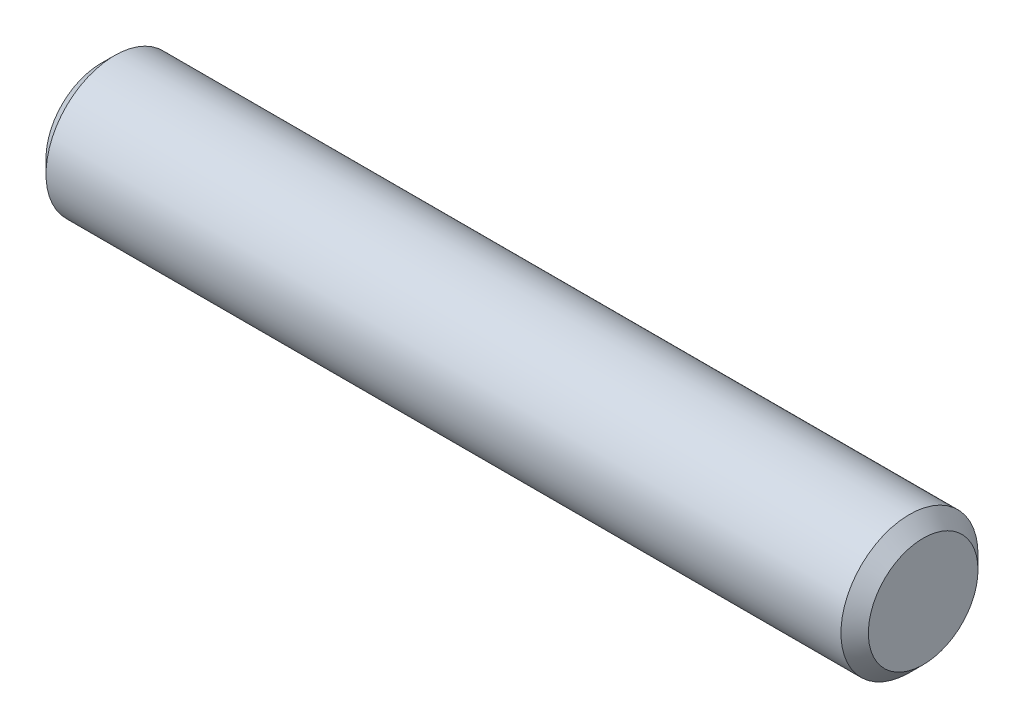
SolidWorks part; units mm, degrees
ref_plane "Front" through (0, 0, 0) normal (0, 0, 1) x (1, 0, 0)
ref_plane "Top" through (0, 0, 0) normal (0, 1, 0) x (1, 0, 0)
ref_plane "Right" through (0, 0, 0) normal (1, 0, 0) x (0, 0, -1)
sketch "Sketch1" plane through (0, 0, 0) normal (0, 0, 1) x (1, 0, 0)
  line L0 (-19.05, 0) -> (19.05, 0) construction
  line L1 (19.05, 3.175) -> (19.05, -3.175) construction
  line L2 (-19.05, 3.175) -> (-19.05, -3.175) construction
  dimension "Length" = 38.1
  dimension "Diameter" = 6.35
sketch "Sketch2" plane through (0, 0, 0) normal (1, 0, 0) x (0, 0, -1)
  circle A0 centre (0, 0) radius 3.175
extrude "Extrude1" add sketch "Sketch2" against normal up to vertex (19.05 mm away) and the other way up to vertex (19.05 mm away) up to point (-19.05, 3.175, 0) other way up to point (19.05, 3.175, 0)
chamfer "Chamfer1" distance 0.635 angle 45 2 edges at (19.05, 0, -3.175) (-19.05, 0, -3.175)
equation "\"D1@Chamfer1\" = \"Diameter@Sketch1\"*.1"
